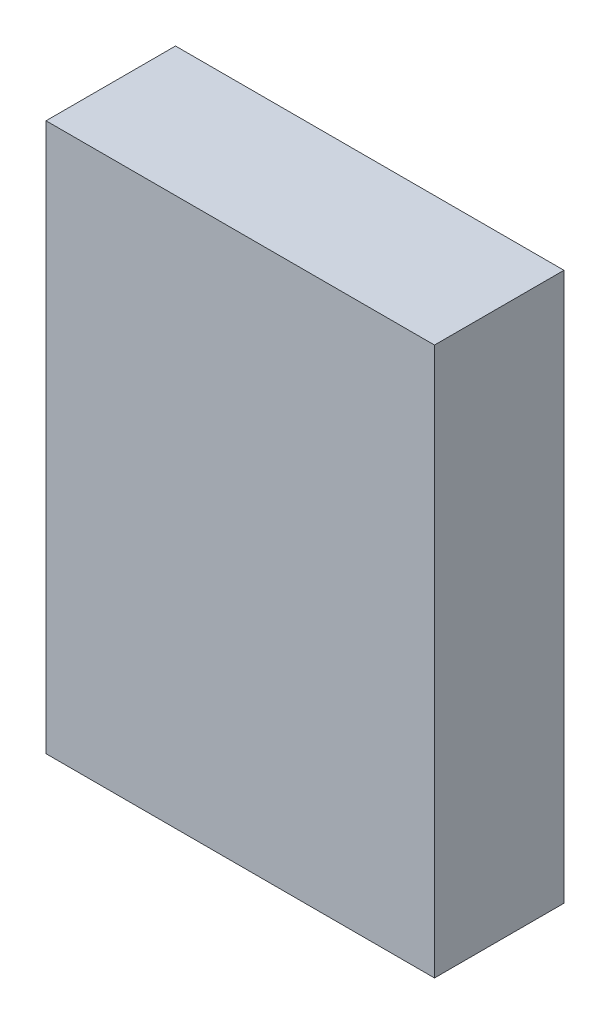
SolidWorks part; units mm, degrees
ref_plane "Front Plane" through (0, 0, 0) normal (0, 0, 1) x (1, 0, 0)
ref_plane "Top Plane" through (0, 0, 0) normal (0, 1, 0) x (1, 0, 0)
ref_plane "Right Plane" through (0, 0, 0) normal (1, 0, 0) x (0, 0, -1)
sketch "Sketch1" plane through (0, 0, 0) normal (0, 0, 1) x (1, 0, 0)
  line L1 (0, 0) -> (9, 0)
  line L2 (0, 0) -> (0, 12.7)
  line L3 (0, 12.7) -> (9, 12.7)
  line L4 (9, 0) -> (9, 12.7)
  dimension "D1" = 12.7
  dimension "D2" = 9
extrude "Boss-Extrude1" add sketch "Sketch1" along normal blind 3
